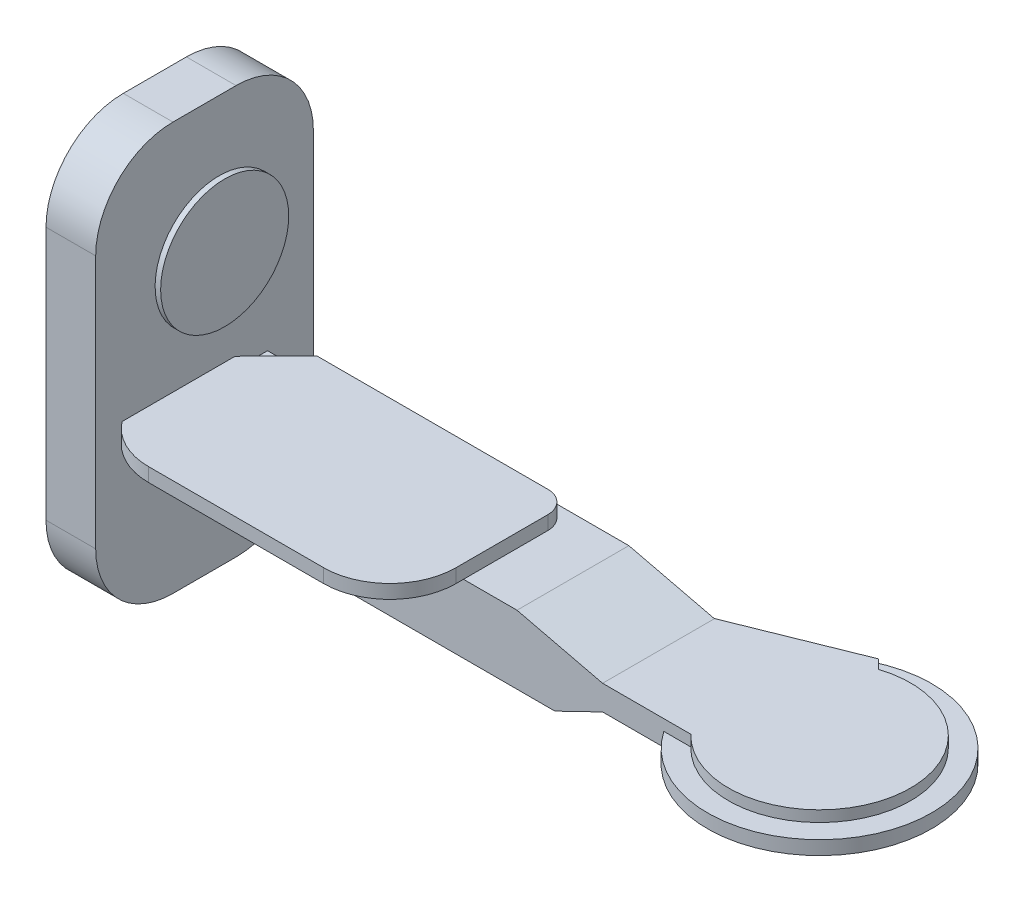
SolidWorks part; units mm, degrees
ref_plane "Front Plane" through (0, 0, 0) normal (0, 0, 1) x (1, 0, 0)
ref_plane "Top Plane" through (0, 0, 0) normal (0, 1, 0) x (1, 0, 0)
ref_plane "Right Plane" through (0, 0, 0) normal (1, 0, 0) x (0, 0, -1)
sketch "Sketch2" plane through (0, 0, 0) normal (0, 1, 0) x (1, 0, 0)
  circle A0 centre (0, 0) radius 203
  dimension "D1" = 406
extrude "Boss-Extrude1" add sketch "Sketch2" along normal blind 25
sketch "Sketch3" plane through (0, 25, 0) normal (0, 1, 0) x (1, 0, 0)
  circle A0 centre (0, 0) radius 165
extrude "Boss-Extrude4" add sketch "Sketch3" along normal blind 20
sketch "Sketch8" plane through (0, 45, 0) normal (0, 1, 0) x (1, 0, 0)
  line L0 (-36.2185, 88.3732) -> (-36.2185, 142.8459)
  line L1 (-36.2185, 142.8459) -> (-66.9318, 173.5592)
  line L2 (-66.9318, 173.5592) -> (-278.448, 88.3732)
  line L3 (-278.448, 88.3732) -> (-278.448, -114.6268)
  line L4 (-278.448, -114.6268) -> (-36.2185, -114.6268)
  line L5 (-36.2185, -114.6268) -> (-36.2185, 88.3732)
  dimension "D1" = 203
  dimension "D2" = 228.0258
extrude "Boss-Extrude6" add sketch "Sketch8" against normal blind 45
ref_plane "Plane1" through (0, 0, -88) normal (0, 0, 1) x (1, 0, 0)
sketch "Sketch11" plane through (0, 0, -88) normal (0, 0, 1) x (1, 0, 0)
  line L0 (-278.448, 0) -> (-364.8263, -41.8902)
  line L2 (-433.5301, 82.1098) -> (-278.448, 45)
  line L3 (-364.8263, -41.8902) -> (-773.8263, -41.8902)
  line L4 (-773.8263, -41.8902) -> (-773.8263, 82.1098)
  line L5 (-773.8263, 82.1098) -> (-433.5301, 82.1098)
  line L6 (-278.448, 45) -> (-278.448, 0)
  dimension "D1" = 409
  dimension "D2" = 124
  dimension "D3" = 96
extrude "Boss-Extrude7" add sketch "Sketch11" along normal up to surface (202.6268 mm away) up to face at (-188.2238, 23.3333, 114.6268)
sketch "Sketch12" plane through (0, 0, -88) normal (0, 0, -1) x (-1, 0, 0)
  line L0 (773.8263, 82.1098) -> (773.8263, -41.8902) construction
  line L1 (773.8263, -21.8902) -> (373.8263, -21.8902)
  line L2 (773.8263, -21.8902) -> (773.8263, 62.1098)
  line L3 (773.8263, 62.1098) -> (373.8263, 62.1098)
  line L4 (373.8263, -21.8902) -> (373.8263, 62.1098)
  line L5 (773.8263, -41.8902) -> (364.8263, -41.8902) construction
  line L6 (433.5301, 82.1098) -> (773.8263, 82.1098) construction
  dimension "D1" = 20
  dimension "D2" = 20
  dimension "D3" = 400
extrude "Cut-Extrude2" cut sketch "Sketch12" against normal blind 195
sketch "Sketch13" plane through (0, -41.8902, 0) normal (0, -1, 0) x (1, 0, 0)
  circle A0 centre (-572.874, 13.9727) radius 65
  dimension "D1" = 130
extrude "Boss-Extrude8" add sketch "Sketch13" along normal blind 5
sketch "Sketch14" plane through (0, -46.8902, 0) normal (0, -1, 0) x (1, 0, 0)
  circle A0 centre (-572.874, 13.9727) radius 59.5
extrude "Boss-Extrude9" add sketch "Sketch14" along normal blind 14
sketch "Sketch15" plane through (0, 82.1098, 0) normal (0, 1, 0) x (1, 0, 0)
  circle A0 centre (-702.4415, -14.6274) radius 21.0463
  circle A1 centre (-628.8926, -14.6274) radius 21.0463
  circle A2 centre (-572.1226, -14.6274) radius 21.0463
extrude "Boss-Extrude10" add sketch "Sketch15" along normal blind 14
sketch "Sketch16" plane through (0, 96.1098, 0) normal (0, 1, 0) x (1, 0, 0)
  line L0 (-556.4974, 64.0699) -> (-974.1765, 64.0699)
  line L1 (-974.1765, 64.0699) -> (-1038.1494, 0.097)
  line L2 (-1073.2966, -84.7558) -> (-1073.2966, -142.0772)
  line L3 (-953.2966, -262.0772) -> (-636.4974, -262.0772)
  line L4 (-516.4974, -142.0772) -> (-516.4974, 24.0699)
  arc A0 (-1038.1494, 0.097) -> (-1073.2966, -84.7558) centre (-953.2966, -84.7558) ccw
  arc A1 (-1073.2966, -142.0772) -> (-953.2966, -262.0772) centre (-953.2966, -142.0772) ccw
  arc A2 (-636.4974, -262.0772) -> (-516.4974, -142.0772) centre (-636.4974, -142.0772) ccw
  arc A3 (-556.4974, 64.0699) -> (-516.4974, 24.0699) centre (-556.4974, 24.0699) cw
  dimension "D1" = 120
  dimension "D2" = 120
  dimension "D3" = 120
  dimension "D4" = 40
extrude "Boss-Extrude11" add sketch "Sketch16" along normal blind 25
sketch "Sketch17" plane through (-1073.2966, 0, 0) normal (-1, 0, 0) x (0, 0, 1)
  line L1 (8.7686, 544.9236) -> (123.1734, 544.9236)
  line L2 (-131.2314, 404.9236) -> (-131.2314, -54.7599)
  line L3 (8.7686, -194.7599) -> (123.1734, -194.7599)
  line L4 (263.1734, 404.9236) -> (263.1734, -54.7599)
  arc A0 (8.7686, 544.9236) -> (-131.2314, 404.9236) centre (8.7686, 404.9236) ccw
  arc A1 (123.1734, 544.9236) -> (263.1734, 404.9236) centre (123.1734, 404.9236) cw
  arc A2 (123.1734, -194.7599) -> (263.1734, -54.7599) centre (123.1734, -54.7599) ccw
  arc A3 (-131.2314, -54.7599) -> (8.7686, -194.7599) centre (8.7686, -54.7599) ccw
  dimension "D1" = 140
extrude "Boss-Extrude12" add sketch "Sketch17" along normal blind 65 and the other way blind 25
ref_plane "Plane2" through (0, 0, -23.2314) normal (0, 0, -1) x (-1, 0, 0)
sketch "Sketch19" plane through (0, 0, -23.2314) normal (0, 0, -1) x (-1, 0, 0)
  line L0 (1052.9312, -16.7525) -> (985.0635, 100.4388)
  line L1 (985.0635, 100.4388) -> (1052.9312, 100.4388)
  line L2 (1052.9312, 100.4388) -> (1052.9312, -16.7525)
extrude "Boss-Extrude13" add sketch "Sketch19" along normal blind 25 and the other way blind 15
fillet "Fillet1" radius 10 2 edges at (-1048.2966, -8.7497, -28.2314) (-987.5706, 96.1098, -28.2314)
sketch "Sketch20" plane through (-1048.2966, 0, 0) normal (1, 0, 0) x (0, 0, -1)
  circle A0 centre (-39.4967, 302.8783) radius 116.015
extrude "Boss-Extrude14" add sketch "Sketch20" along normal blind 10
